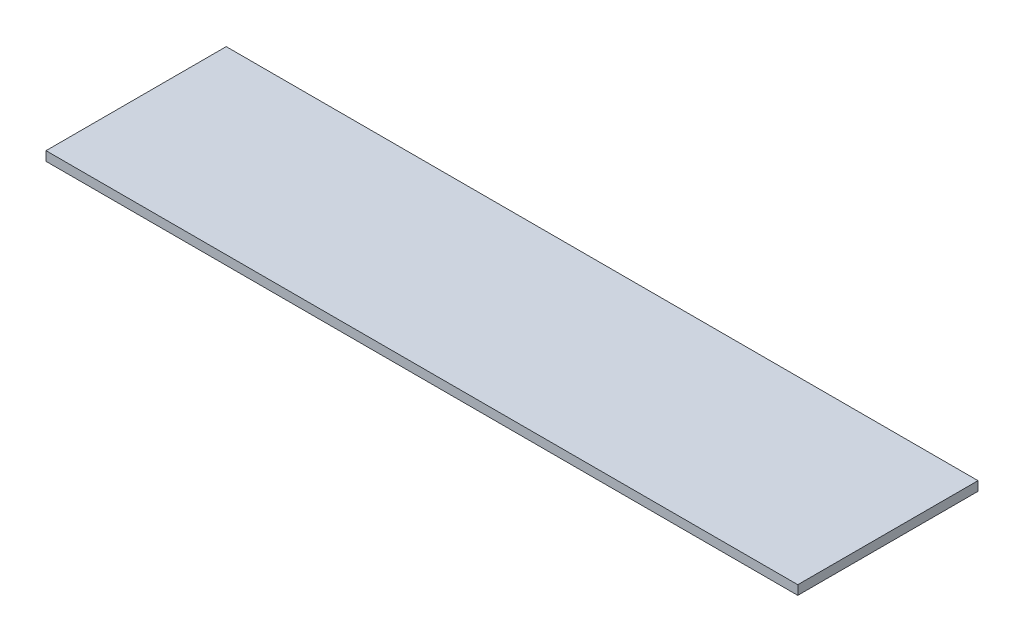
SolidWorks part; units mm, degrees
material "Pine"
ref_plane "Front Plane" through (0, 0, 0) normal (0, 0, 1) x (1, 0, 0)
ref_plane "Top Plane" through (0, 0, 0) normal (0, 1, 0) x (1, 0, 0)
ref_plane "Right Plane" through (0, 0, 0) normal (1, 0, 0) x (0, 0, -1)
sketch "Sketch1" plane through (0, 0, 0) normal (0, 1, 0) x (1, 0, 0)
  line L1 (-730, 175) -> (730, 175)
  line L2 (-730, 175) -> (-730, -175)
  line L3 (-730, -175) -> (730, -175)
  line L4 (730, 175) -> (730, -175)
  line L5 (-730, 175) -> (730, -175) construction
  line L6 (-730, -175) -> (730, 175) construction
  point P0 (0, 0)
  dimension "D1" = 1460
  dimension "D2" = 350
extrude "Boss-Extrude1" add sketch "Sketch1" along normal blind 18
